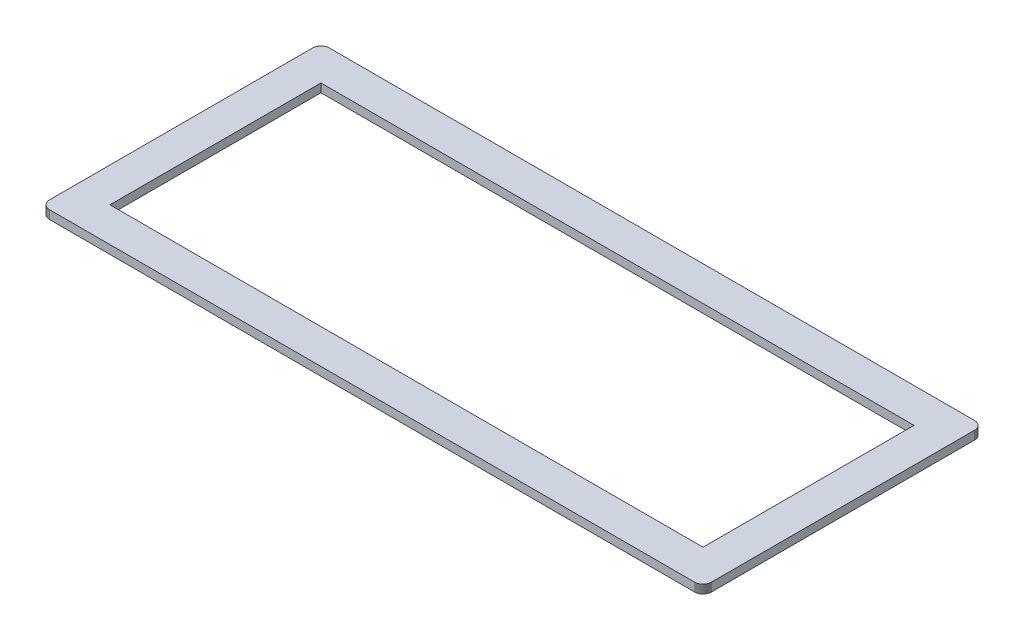
SolidWorks part; units mm, degrees
ref_plane "Front Plane" through (0, 0, 0) normal (0, 0, 1) x (1, 0, 0)
ref_plane "Top Plane" through (0, 0, 0) normal (0, 1, 0) x (1, 0, 0)
ref_plane "Right Plane" through (0, 0, 0) normal (1, 0, 0) x (0, 0, -1)
sketch "Sketch1" plane through (0, 0, 0) normal (0, 1, 0) x (1, 0, 0)
  line L0 (382.958, 164.299) -> (383.35, 164.284)
  line L1 (383.35, 164.284) -> (383.741, 164.237)
  line L2 (383.741, 164.237) -> (384.126, 164.162)
  line L3 (384.126, 164.162) -> (384.503, 164.055)
  line L4 (384.503, 164.055) -> (384.87, 163.919)
  line L5 (384.87, 163.919) -> (385.226, 163.755)
  line L6 (385.226, 163.755) -> (385.572, 163.564)
  line L7 (385.572, 163.564) -> (385.897, 163.344)
  line L8 (385.897, 163.344) -> (386.203, 163.102)
  line L9 (386.203, 163.102) -> (386.493, 162.834)
  line L10 (386.493, 162.834) -> (386.761, 162.547)
  line L11 (386.761, 162.547) -> (387.004, 162.238)
  line L12 (387.004, 162.238) -> (387.223, 161.913)
  line L13 (387.223, 161.913) -> (387.414, 161.569)
  line L14 (387.414, 161.569) -> (387.576, 161.212)
  line L15 (387.576, 161.212) -> (387.713, 160.845)
  line L16 (387.713, 160.845) -> (387.819, 160.467)
  line L17 (387.819, 160.467) -> (387.897, 160.082)
  line L18 (387.897, 160.082) -> (387.943, 159.693)
  line L19 (387.943, 159.693) -> (387.96, 159.299)
  line L20 (387.96, 159.299) -> (387.96, 5.2724)
  line L21 (387.96, 5.2724) -> (387.943, 4.881)
  line L22 (387.943, 4.881) -> (387.897, 4.491)
  line L23 (387.897, 4.491) -> (387.819, 4.1066)
  line L24 (387.819, 4.1066) -> (387.713, 3.7276)
  line L25 (387.713, 3.7276) -> (387.576, 3.3597)
  line L26 (387.576, 3.3597) -> (387.414, 3.0041)
  line L27 (387.414, 3.0041) -> (387.223, 2.661)
  line L28 (387.223, 2.661) -> (387.004, 2.3344)
  line L29 (387.004, 2.3344) -> (386.761, 2.0257)
  line L30 (386.761, 2.0257) -> (386.493, 1.7377)
  line L31 (386.493, 1.7377) -> (386.203, 1.4704)
  line L32 (386.203, 1.4704) -> (385.897, 1.2278)
  line L33 (385.897, 1.2278) -> (385.572, 1.0101)
  line L34 (385.572, 1.0101) -> (385.226, 0.8186)
  line L35 (385.226, 0.8186) -> (384.87, 0.6546)
  line L36 (384.87, 0.6546) -> (384.503, 0.5181)
  line L37 (384.503, 0.5181) -> (384.126, 0.412)
  line L38 (384.126, 0.412) -> (383.741, 0.3349)
  line L39 (383.741, 0.3349) -> (383.35, 0.2894)
  line L40 (383.35, 0.2894) -> (382.958, 0.2729)
  line L41 (382.958, 0.2729) -> (5.096, 0.2729)
  line L42 (5.096, 0.2729) -> (4.7019, 0.2894)
  line L43 (4.7019, 0.2894) -> (4.3119, 0.3349)
  line L44 (4.3119, 0.3349) -> (3.9274, 0.412)
  line L45 (3.9274, 0.412) -> (3.5498, 0.5181)
  line L46 (3.5498, 0.5181) -> (3.1819, 0.6546)
  line L47 (3.1819, 0.6546) -> (2.825, 0.8186)
  line L48 (2.825, 0.8186) -> (2.4819, 1.0101)
  line L49 (2.4819, 1.0101) -> (2.1566, 1.2278)
  line L50 (2.1566, 1.2278) -> (1.848, 1.4704)
  line L51 (1.848, 1.4704) -> (1.5599, 1.7377)
  line L52 (1.5599, 1.7377) -> (1.2926, 2.0257)
  line L53 (1.2926, 2.0257) -> (1.0501, 2.3344)
  line L54 (1.0501, 2.3344) -> (0.831, 2.661)
  line L55 (0.831, 2.661) -> (0.6394, 3.0041)
  line L56 (0.6394, 3.0041) -> (0.4754, 3.3597)
  line L57 (0.4754, 3.3597) -> (0.339, 3.7276)
  line L58 (0.339, 3.7276) -> (0.2329, 4.1066)
  line L59 (0.2329, 4.1066) -> (0.1571, 4.491)
  line L60 (0.1571, 4.491) -> (0.1102, 4.881)
  line L61 (0.1102, 4.881) -> (0.0951, 5.2737)
  line L62 (0.0951, 5.2737) -> (0.0951, 159.299)
  line L63 (0.0951, 159.299) -> (0.1102, 159.693)
  line L64 (0.1102, 159.693) -> (0.1571, 160.082)
  line L65 (0.1571, 160.082) -> (0.2329, 160.467)
  line L66 (0.2329, 160.467) -> (0.339, 160.845)
  line L67 (0.339, 160.845) -> (0.4754, 161.212)
  line L68 (0.4754, 161.212) -> (0.6394, 161.569)
  line L69 (0.6394, 161.569) -> (0.831, 161.913)
  line L70 (0.831, 161.913) -> (1.0501, 162.238)
  line L71 (1.0501, 162.238) -> (1.2926, 162.547)
  line L72 (1.2926, 162.547) -> (1.5599, 162.834)
  line L73 (1.5599, 162.834) -> (1.848, 163.102)
  line L74 (1.848, 163.102) -> (2.1566, 163.344)
  line L75 (2.1566, 163.344) -> (2.4819, 163.564)
  line L76 (2.4819, 163.564) -> (2.825, 163.755)
  line L77 (2.825, 163.755) -> (3.1819, 163.919)
  line L78 (3.1819, 163.919) -> (3.5498, 164.055)
  line L79 (3.5498, 164.055) -> (3.9274, 164.162)
  line L80 (3.9274, 164.162) -> (4.3119, 164.237)
  line L81 (4.3119, 164.237) -> (4.7019, 164.284)
  line L82 (4.7019, 164.284) -> (5.096, 164.299)
  line L83 (5.096, 164.299) -> (382.958, 164.299)
  line L84 (20.2944, 144.099) -> (367.757, 144.099)
  line L85 (367.757, 144.099) -> (367.757, 20.4735)
  line L86 (367.757, 20.4735) -> (20.2944, 20.4735)
  line L87 (20.2944, 20.4735) -> (20.2944, 144.099)
extrude "Boss-Extrude1" add sketch "Sketch1" along normal blind 5
